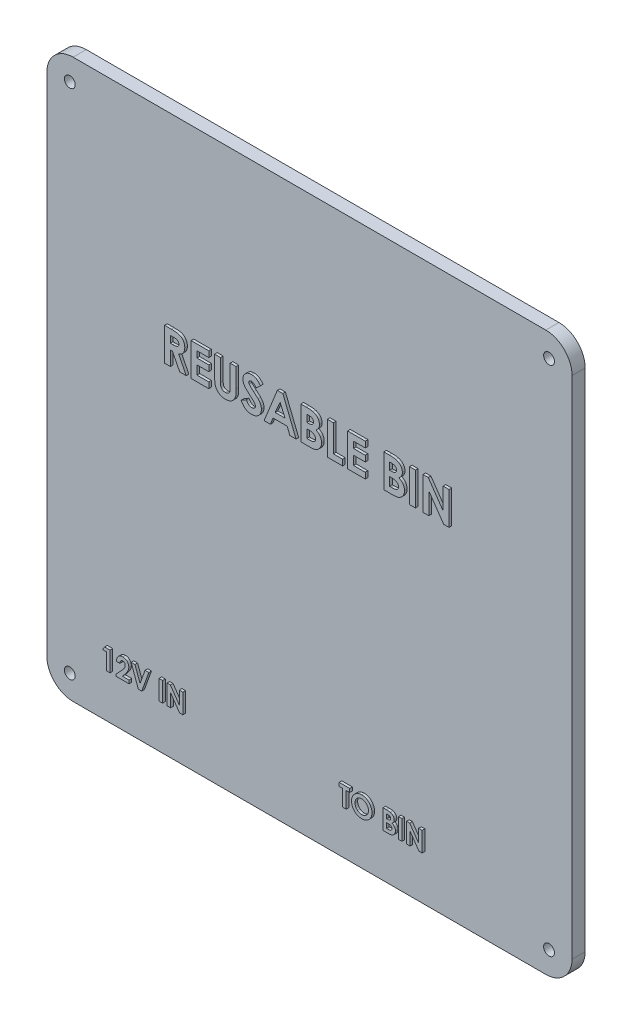
SolidWorks part; units mm, degrees
ref_plane "Front Plane" through (0, 0, 0) normal (0, 0, 1) x (1, 0, 0)
ref_plane "Top Plane" through (0, 0, 0) normal (0, 1, 0) x (1, 0, 0)
ref_plane "Right Plane" through (0, 0, 0) normal (1, 0, 0) x (0, 0, -1)
sketch "Sketch1" plane through (0, 0, 0) normal (0, 0, 1) x (1, 0, 0)
  line L0 (-72, 0) -> (72, 0)
  line L1 (80, 8) -> (80, 162)
  line L2 (72, 170) -> (-72, 170)
  line L3 (-80, 162) -> (-80, 8)
  arc A0 (-80, 8) -> (-72, 0) centre (-72, 8) ccw
  arc A1 (72, 0) -> (80, 8) centre (72, 8) ccw
  arc A2 (80, 162) -> (72, 170) centre (72, 162) ccw
  arc A3 (-72, 170) -> (-80, 162) centre (-72, 162) ccw
extrude "Lid" add sketch "Sketch1" along normal blind 4
sketch "Sketch2" plane through (0, 0, 0) normal (0, 0, 1) x (1, 0, 0)
  circle A0 centre (-73, 7) radius 1.65
  circle A1 centre (73, 7) radius 1.65
  circle A2 centre (-73, 163) radius 1.65
  circle A3 centre (73, 163) radius 1.65
extrude "Screw holes" cut sketch "Sketch2" along normal through all
ref_plane "P1_Front_-3" through (0, 0, -3) normal (0, 0, 1) x (1, 0, 0)
sketch "Sketch3" plane through (0, 0, -3) normal (0, 0, 1) x (1, 0, 0)
  line L1 (-15, 3.3) -> (15, 3.3)
  line L2 (-15, 3.3) -> (-15, 5.3)
  line L3 (-15, 5.3) -> (15, 5.3)
  line L4 (15, 3.3) -> (15, 5.3)
  line L6 (-15, 164.7) -> (15, 164.7)
  line L7 (-15, 164.7) -> (-15, 166.7)
  line L8 (-15, 166.7) -> (15, 166.7)
  line L9 (15, 164.7) -> (15, 166.7)
  line L11 (-76.7, 70) -> (-74.7, 70)
  line L12 (-76.7, 70) -> (-76.7, 100)
  line L13 (-76.7, 100) -> (-74.7, 100)
  line L14 (-74.7, 70) -> (-74.7, 100)
  line L16 (74.7, 70) -> (76.7, 70)
  line L17 (74.7, 70) -> (74.7, 100)
  line L18 (74.7, 100) -> (76.7, 100)
  line L19 (76.7, 70) -> (76.7, 100)
extrude "Locating tabs" add sketch "Sketch3" along normal blind 3
ref_plane "P2_Front_4" through (0, 0, 4) normal (0, 0, 1) x (1, 0, 0)
sketch "Sketch4" plane through (0, 0, 4) normal (0, 0, 1) x (1, 0, 0)
  text T0 "REUSABLE BIN" font "Century Gothic" height 10
  text T1 "12V IN" font "Century Gothic" height 6
  text T2 "TO BIN" font "Century Gothic" height 6
extrude "Labels (raised)" add sketch "Sketch4" along normal blind 0.8
